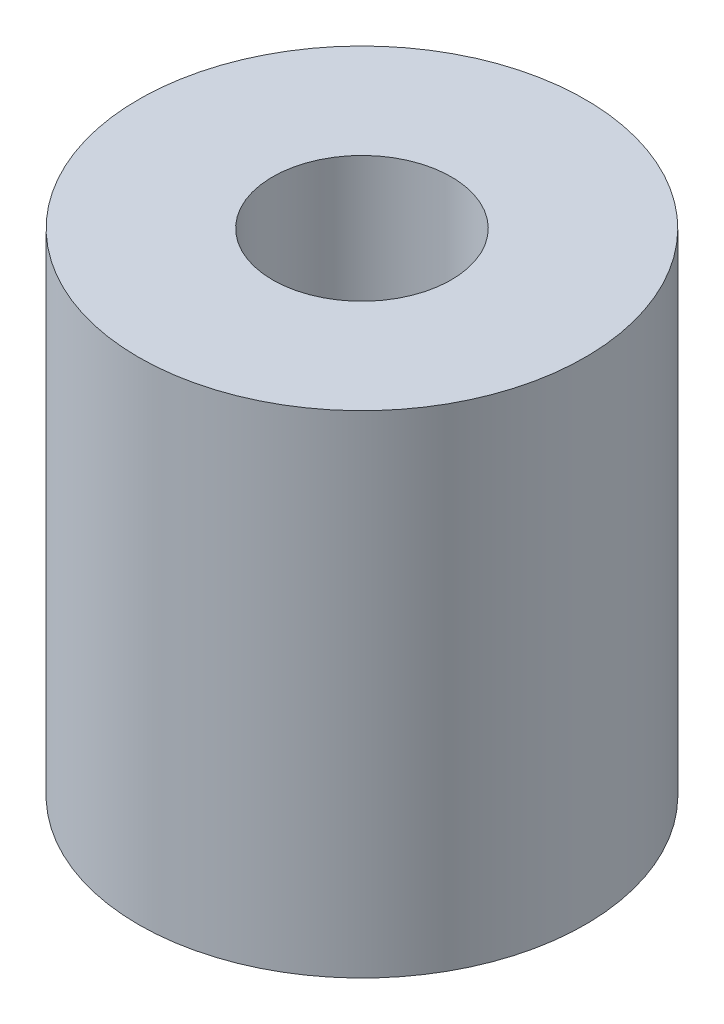
SolidWorks part; units mm, degrees
ref_plane "Front Plane" through (0, 0, 0) normal (0, 0, 1) x (1, 0, 0)
ref_plane "Top Plane" through (0, 0, 0) normal (0, 1, 0) x (1, 0, 0)
ref_plane "Right Plane" through (0, 0, 0) normal (1, 0, 0) x (0, 0, -1)
sketch "Sketch1" plane through (0, 0, 0) normal (0, 1, 0) x (1, 0, 0)
  circle A0 centre (0, 0) radius 1
  circle A1 centre (0, 0) radius 2.5
extrude "Boss-Extrude1" add sketch "Sketch1" along normal blind 5.5
